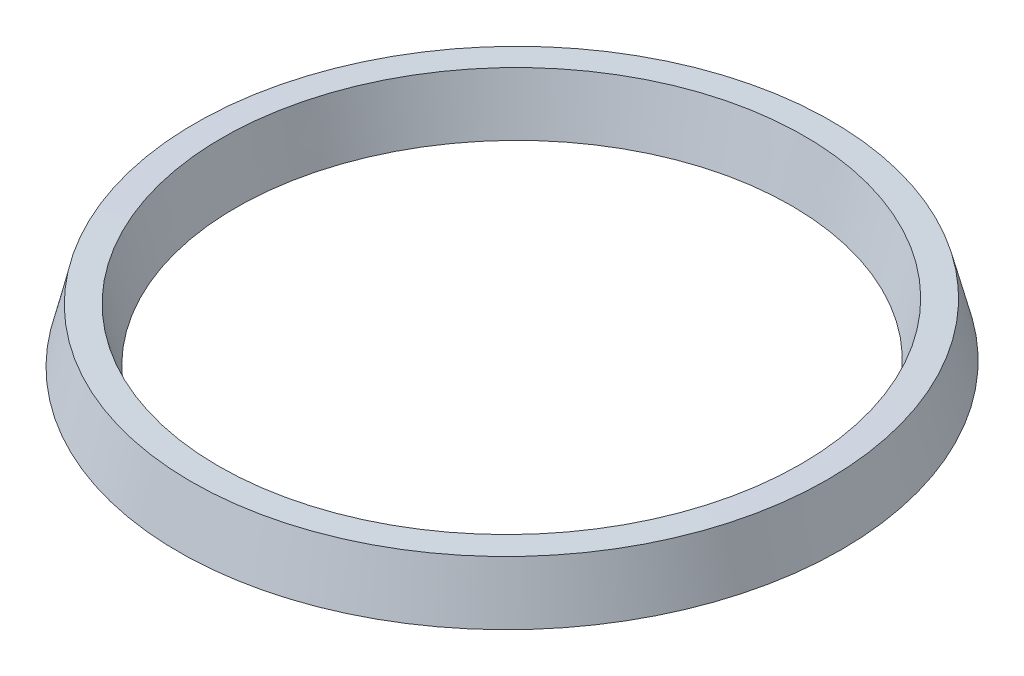
SolidWorks part; units mm, degrees
ref_plane "Front Plane" through (0, 0, 0) normal (0, 0, 1) x (1, 0, 0)
ref_plane "Top Plane" through (0, 0, 0) normal (0, 1, 0) x (1, 0, 0)
ref_plane "Right Plane" through (0, 0, 0) normal (1, 0, 0) x (0, 0, -1)
sketch "Sketch1" plane through (0, 0, 0) normal (0, 0, 1) x (1, 0, 0)
  line L0 (0, 0) -> (-67.7676, -0.8055) construction
  line L1 (-67.7676, -0.8055) -> (-67.8718, 7.9589) construction
  line L2 (0, 0) -> (0, 7.9589) construction
  line L3 (-3, 6) -> (3, 6)
  line L4 (-3, 6) -> (-5.8612, -6)
  line L5 (-5.8612, -6) -> (-2.8612, -6)
  line L6 (3, 6) -> (6.1388, -6)
  line L7 (6.1388, -6) -> (3.1388, -6)
  line L8 (-2.8612, -6) -> (-1.737, -1.2851)
  line L9 (3.1388, -6) -> (1.8952, -1.2455)
  arc A0 (-1.737, -1.2851) -> (1.8952, -1.2455) centre (0.084, -1.7193) cw
  dimension "D1" = 6
  dimension "D2" = 3
  dimension "D3" = 3
  dimension "D4" = 6
  dimension "D5" = 12
  dimension "D6" = 12
  dimension "D7" = 67.8718
  dimension "D8" = 8.6897
  dimension "D9" = 3
  dimension "D10" = 12
  dimension "D11" = 3
revolve "Revolve1" add sketch "Sketch1" angle 360 about L1
